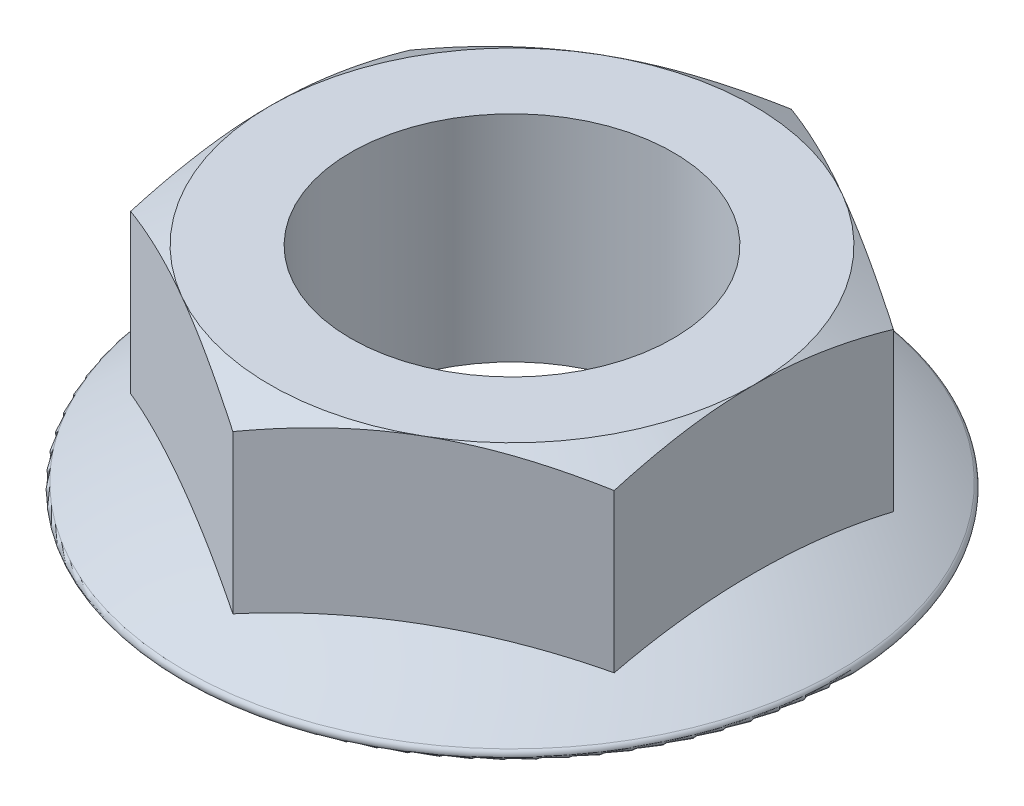
SolidWorks part; units mm, degrees
ref_plane "Front Plane" through (0, 0, 0) normal (0, 0, 1) x (1, 0, 0)
ref_plane "Top Plane" through (0, 0, 0) normal (0, 1, 0) x (1, 0, 0)
ref_plane "Right Plane" through (0, 0, 0) normal (1, 0, 0) x (0, 0, -1)
sketch "Sketch1" plane through (0, 0, 0) normal (0, 1, 0) x (1, 0, 0)
  line L1 (0, -25.9808) -> (22.5, -12.9904)
  line L2 (22.5, -12.9904) -> (22.5, 12.9904)
  line L3 (22.5, 12.9904) -> (0, 25.9808)
  line L4 (0, 25.9808) -> (-22.5, 12.9904)
  line L5 (-22.5, 12.9904) -> (-22.5, -12.9904)
  line L6 (-22.5, -12.9904) -> (0, -25.9808)
  circle A0 centre (0, 0) radius 22.5 construction
  dimension "D1" = 45
extrude "Boss-Extrude1" add sketch "Sketch1" along normal blind 20 contours L1 L2 L3 L4 L5 L6
sketch "Sketch2" plane through (0, 0, 0) normal (1, 0, 0) x (0, 0, -1)
  line L0 (0, 0) -> (0, -50000) construction
  line L1 (0, 0) -> (50000, 0) construction
  line L2 (-12.9904, 0) -> (12.9904, 0) construction
  line L3 (0, 9.2142) -> (0, 0)
  line L4 (0, 0) -> (31.95, 0)
  arc A0 (31.95, 0) -> (0, 9.2142) centre (0, -50.7858) ccw
  point P7 (0, 0)
  dimension "D2" = 60
  dimension "D1" = 31.95
revolve "Revolve1" add sketch "Sketch2" angle 360 about L0
fillet "Fillet1" radius 0.5 1 edges at (0, 0, 31.95)
hole_wizard "Ø1.0mm Dowel Hole1" positions "Sketch3" profile "Sketch4" hole size "Ø1.0" standard "ANSI Metric" end condition up to next
sketch "Sketch3" plane through (0, 20, 0) normal (0, 1, 0) x (1, 0, 0)
  point P0 (0, 0)
sketch "Sketch4" plane through (0, 20, 0) normal (1, 0, 0) x (0, 0, 1)
  line L0 (0, 0) -> (0, 20)
  line L1 (0, 20) -> (15, 20)
  line L2 (15, 20) -> (15, 0)
  line L5 (15, 0) -> (0, 0)
  line L11 (0, -6.35) -> (0, 107.95) construction
  dimension "Thru Hole Dia." = 30
  dimension "Thru Hole Depth" = 20
cosmetic thread "Cosmetic Thread1" parameters "D2"=33
cosmetic thread "Cosmetic Thread2" parameters "D2"=33
sketch "Sketch6" plane through (0, 0, 0) normal (0, 0, 1) x (1, 0, 0)
  line L0 (0, 0) -> (0, -50000) construction
  line L1 (22.5, 20) -> (28.5, 20)
  line L3 (28.5, 20) -> (28.5, 16.5359)
  line L5 (28.5, 16.5359) -> (22.5, 20)
  dimension "D1" = 30
  dimension "D2" = 6
revolve "Cut-Revolve2" cut sketch "Sketch6" angle 360 about L0
